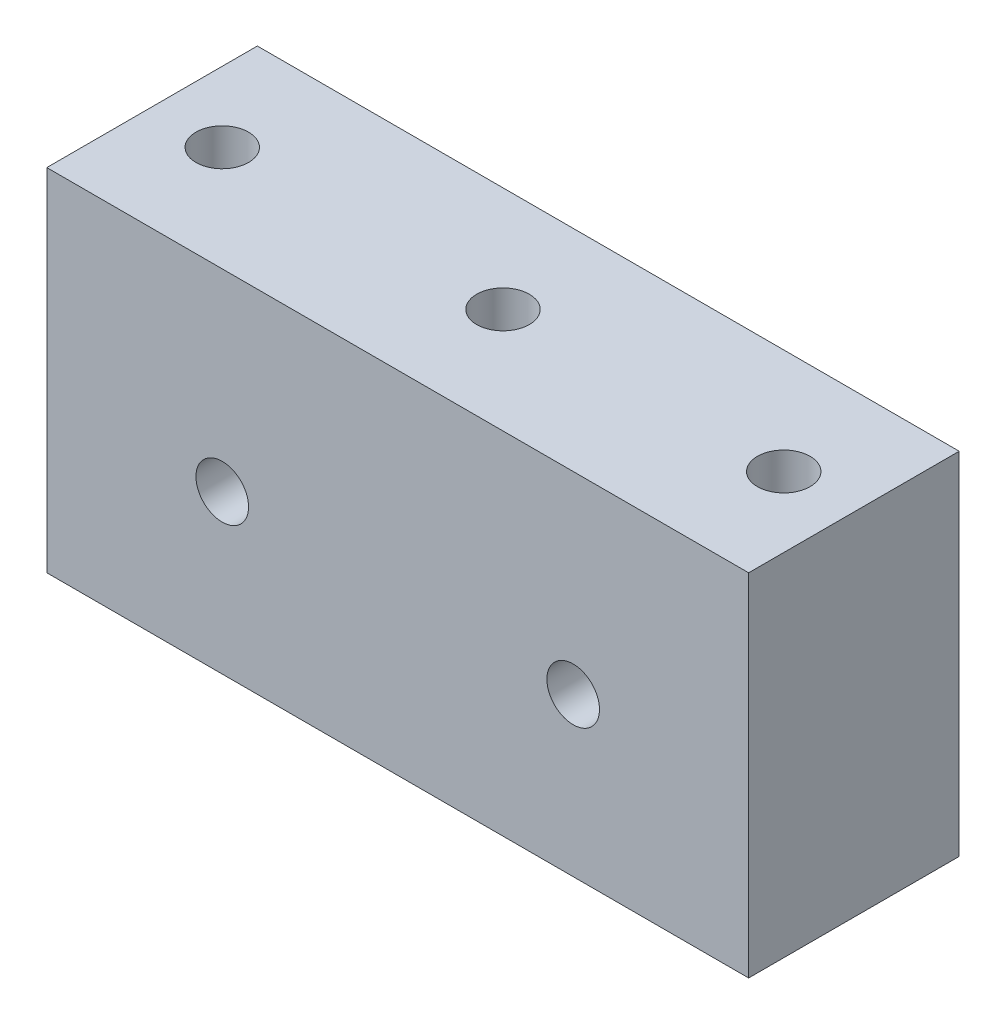
SolidWorks part; units mm, degrees
ref_plane "Front Plane" through (0, 0, 0) normal (0, 0, 1) x (1, 0, 0)
ref_plane "Top Plane" through (0, 0, 0) normal (0, 1, 0) x (1, 0, 0)
ref_plane "Right Plane" through (0, 0, 0) normal (1, 0, 0) x (0, 0, -1)
sketch "Sketch1" plane through (0, 0, 0) normal (0, 1, 0) x (1, 0, 0)
  line L0 (0, 0) -> (-16, 0) construction
  line L1 (-20, 6) -> (20, 6)
  line L2 (-20, 6) -> (-20, -6)
  line L3 (-20, -6) -> (20, -6)
  line L4 (20, 6) -> (20, -6)
  line L5 (-20, 6) -> (20, -6) construction
  line L6 (-20, -6) -> (20, 6) construction
  line L7 (0, -55) -> (0, 55) construction
  circle A0 centre (0, 0) radius 1.5
  circle A1 centre (-16, 0) radius 1.5
  circle A2 centre (16, 0) radius 1.5
  point P0 (0, 0)
  dimension "D3" = 3
  dimension "D5" = 3
  dimension "D1" = 12
  dimension "D2" = 40
  dimension "D4" = 16
extrude "Boss-Extrude1" add sketch "Sketch1" along normal blind 20
sketch "Sketch2" plane through (0, 0, -6) normal (0, 0, -1) x (-1, 0, 0)
  line L0 (0, 0) -> (0, 9) construction
  line L1 (-20, 0) -> (20, 0) construction
  line L2 (0, 9) -> (10, 9) construction
  circle A0 centre (10, 9) radius 1.5
  circle A1 centre (-10, 9) radius 1.5
  dimension "D3" = 3
  dimension "D1" = 9
  dimension "D2" = 10
extrude "Cut-Extrude1" cut sketch "Sketch2" against normal blind 20
